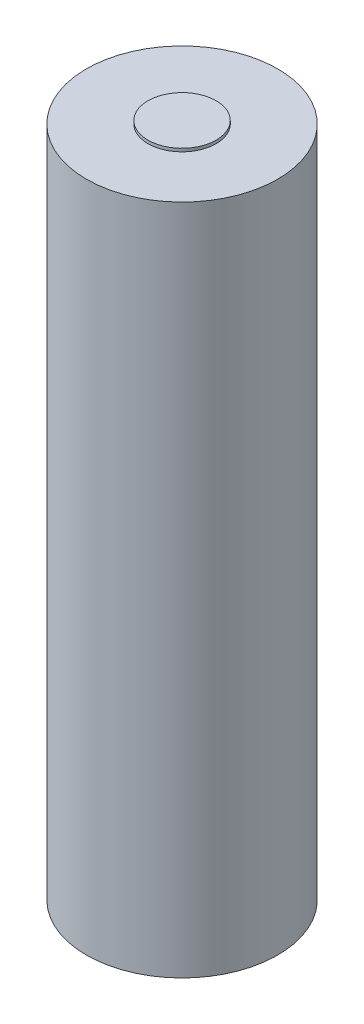
SolidWorks part; units mm, degrees
ref_plane "정면" through (0, 0, 0) normal (0, 0, 1) x (1, 0, 0)
ref_plane "윗면" through (0, 0, 0) normal (0, 1, 0) x (1, 0, 0)
ref_plane "우측면" through (0, 0, 0) normal (1, 0, 0) x (0, 0, -1)
sketch "스케치1" plane through (0, 0, 0) normal (0, 1, 0) x (1, 0, 0)
  circle A0 centre (0, 0) radius 9.25
  dimension "D1" = 18.5
extrude "보스-돌출1" add sketch "스케치1" along normal blind 65
sketch "스케치2" plane through (0, 65, 0) normal (0, 1, 0) x (1, 0, 0)
  circle A0 centre (0, 0) radius 3.3
  dimension "D1" = 6.6
extrude "보스-돌출2" add sketch "스케치2" along normal blind 0.3
